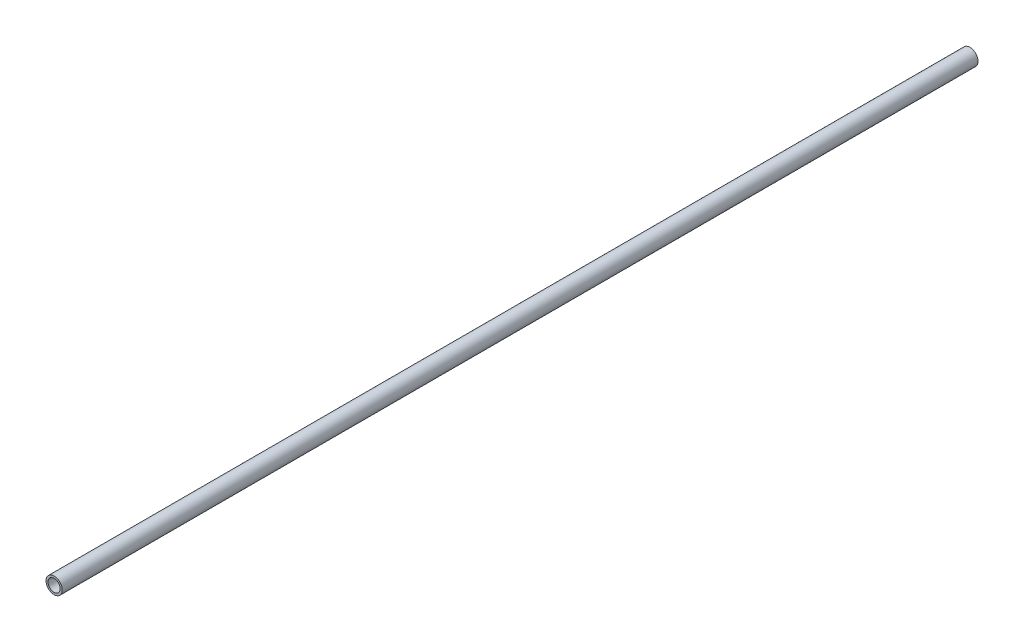
SolidWorks part; units mm, degrees
material "Thornel Mat VMA"
ref_plane "Front Plane" through (0, 0, 0) normal (0, 0, 1) x (1, 0, 0)
ref_plane "Top Plane" through (0, 0, 0) normal (0, 1, 0) x (1, 0, 0)
ref_plane "Right Plane" through (0, 0, 0) normal (1, 0, 0) x (0, 0, -1)
sketch "Sketch1" plane through (0, 0, 0) normal (0, 0, 1) x (1, 0, 0)
  circle A0 centre (0, 0) radius 2
  circle A1 centre (0, 0) radius 1.5
  dimension "D1" = 4
  dimension "D2" = 3
extrude "Boss-Extrude1" add sketch "Sketch1" along normal blind 226.06
